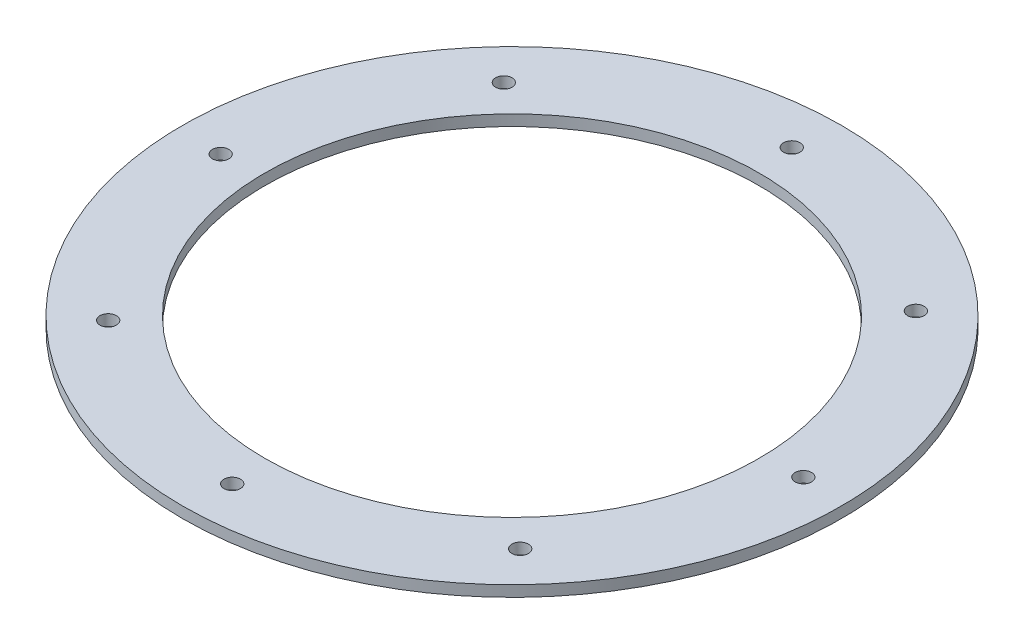
SolidWorks part; units mm, degrees
ref_plane "前视基准面" through (0, 0, 0) normal (0, 0, 1) x (1, 0, 0)
ref_plane "上视基准面" through (0, 0, 0) normal (0, 1, 0) x (1, 0, 0)
ref_plane "右视基准面" through (0, 0, 0) normal (1, 0, 0) x (0, 0, -1)
sketch "草图1" plane through (0, 0, 0) normal (0, 1, 0) x (1, 0, 0)
  circle A0 centre (0, 0) radius 45
  circle A1 centre (0, 0) radius 60
  dimension "D1" = 90
  dimension "D2" = 120
extrude "凸台-拉伸1" add sketch "草图1" along normal blind 2
sketch "草图2" plane through (0, 0, 0) normal (0, -1, 0) x (1, 0, 0)
  circle A0 centre (-51.9893, 1.0538) radius 1.5
extrude "切除-拉伸1" cut sketch "草图2" against normal blind 50
pattern_circular "阵列(圆周)1" count 8 over 360 about axis through (0, 0, 0) along (0, 1, 0) of "切除-拉伸1"
